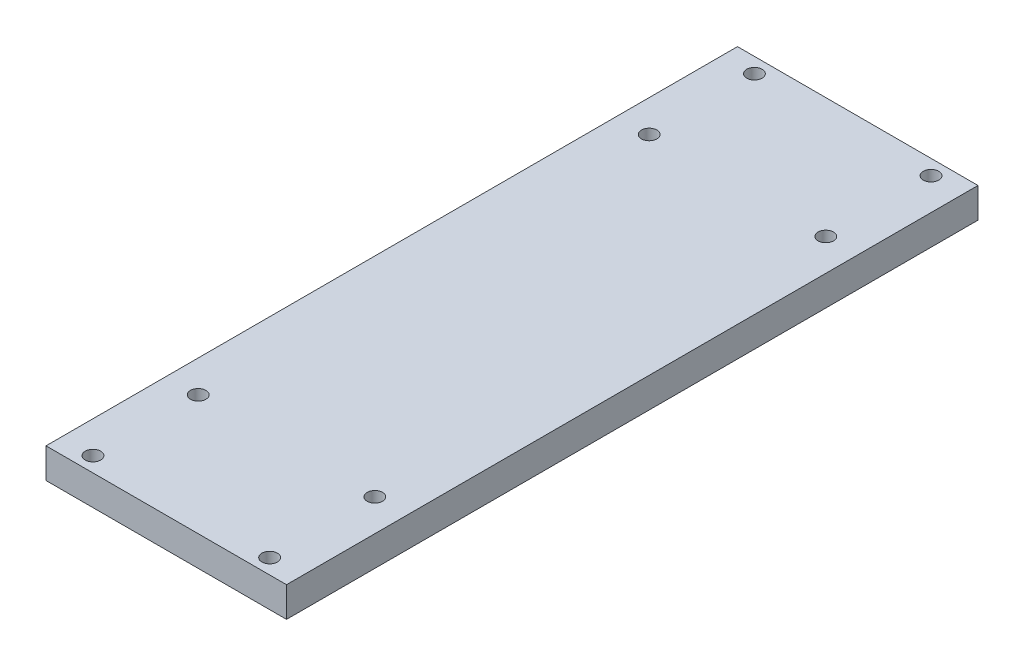
SolidWorks part; units mm, degrees
ref_plane "Front" through (0, 0, 0) normal (0, 0, 1) x (1, 0, 0)
ref_plane "Top" through (0, 0, 0) normal (0, 1, 0) x (1, 0, 0)
ref_plane "Right" through (0, 0, 0) normal (1, 0, 0) x (0, 0, -1)
sketch "Sketch1" plane through (0, 0, 0) normal (0, 1, 0) x (1, 0, 0)
  line L1 (0, 0) -> (101.6, 0)
  line L2 (0, 0) -> (0, 292.1)
  line L3 (0, 292.1) -> (101.6, 292.1)
  line L4 (101.6, 0) -> (101.6, 292.1)
  dimension "D1" = 292.1
  dimension "D2" = 101.6
extrude "Extrude1" add sketch "Sketch1" along normal blind 12.7
hole_wizard "5/16-18 Tapped Hole1" positions "Sketch3" profile "Sketch2" tap size "5/16-18" standard "Ansi Inch" end condition through all
sketch "Sketch3" plane through (0, 12.7, 0) normal (0, 1, 0) x (-1, 0, 0)
  line L0 (-101.6, 0) -> (-101.6, -292.1) construction
  line L1 (0, 0) -> (-101.6, 0) construction
  line L2 (-101.6, -292.1) -> (0, -292.1) construction
  point P0 (-88.1063, -6.35)
  point P11 (-13.4937, -241.3)
  point P13 (-88.1063, -241.3)
  point P15 (-88.1063, -285.75)
  point P17 (-13.4937, -285.75)
  point P22 (-88.1063, -50.8)
  point P24 (-13.4937, -50.8)
  point P26 (-13.4937, -6.35)
  dimension "D1" = 13.4937
  dimension "D2" = 6.35
  dimension "D3" = 74.6125
  dimension "D4" = 44.45
  dimension "D5" = 6.35
  dimension "D6" = 44.45
sketch "Sketch2" plane through (88.1063, 12.7, -6.35) normal (1, 0, 0) x (0, 0, 1)
  line L0 (0, 0) -> (0, 12.7)
  line L1 (0, 12.7) -> (3.2639, 12.7)
  line L2 (3.2639, 12.7) -> (3.2639, 0)
  line L5 (3.2639, 0) -> (0, 0)
  line L11 (0, -6.35) -> (0, 107.95) construction
  dimension "Thru Tap Drill Dia." = 6.5278
  dimension "Thru Tap Drill Depth" = 12.7
cosmetic thread "Hole Thread1" parameters "D2"=7.9375
cosmetic thread "Hole Thread2" parameters "D2"=7.9375
cosmetic thread "Hole Thread3" parameters "D2"=7.9375
cosmetic thread "Hole Thread4" parameters "D2"=7.9375
cosmetic thread "Hole Thread5" parameters "D2"=7.9375
cosmetic thread "Hole Thread6" parameters "D2"=7.9375
cosmetic thread "Hole Thread7" parameters "D2"=7.9375
cosmetic thread "Hole Thread8" parameters "D2"=7.9375
